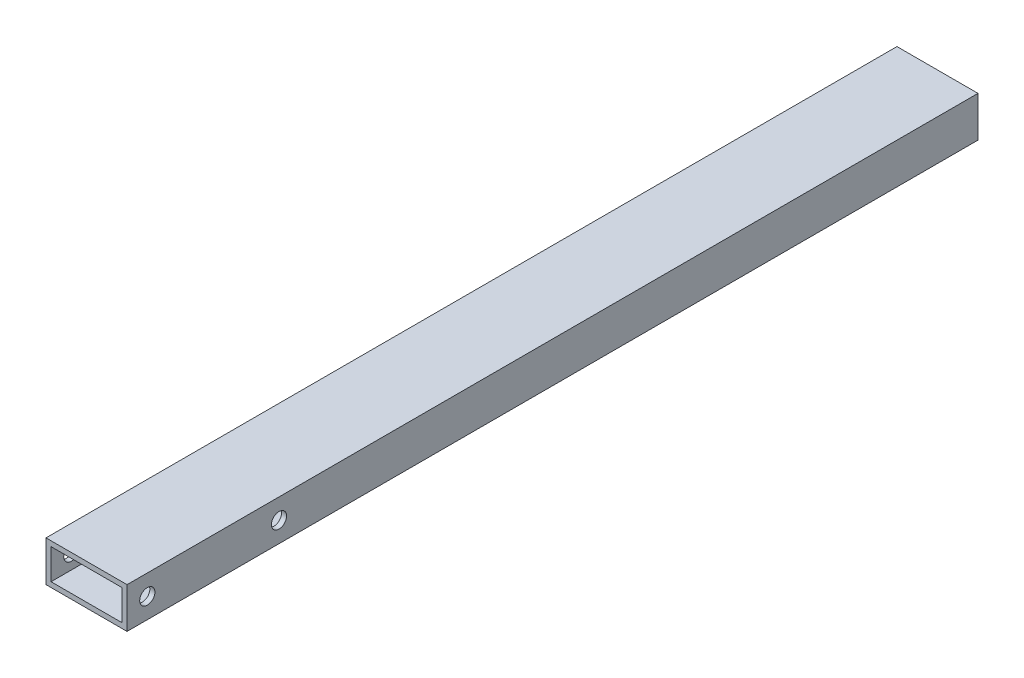
SolidWorks part; units mm, degrees
ref_plane "Front Plane" through (0, 0, 0) normal (0, 0, 1) x (1, 0, 0)
ref_plane "Top Plane" through (0, 0, 0) normal (0, 1, 0) x (1, 0, 0)
ref_plane "Right Plane" through (0, 0, 0) normal (1, 0, 0) x (0, 0, -1)
sketch "Sketch1" plane through (0, 0, 0) normal (0, 0, 1) x (1, 0, 0)
  line L0 (-22.225, 9.525) -> (22.225, 9.525)
  line L1 (-25.4, -12.7) -> (25.4, -12.7)
  line L2 (-25.4, -12.7) -> (-25.4, 12.7)
  line L3 (-25.4, 12.7) -> (25.4, 12.7)
  line L4 (25.4, -12.7) -> (25.4, 12.7)
  line L5 (-25.4, -12.7) -> (25.4, 12.7) construction
  line L6 (-25.4, 12.7) -> (25.4, -12.7) construction
  line L7 (22.225, -9.525) -> (22.225, 9.525)
  line L8 (-22.225, -9.525) -> (22.225, -9.525)
  line L9 (-22.225, -9.525) -> (-22.225, 9.525)
  point P0 (0, 0)
  dimension "D1" = 25.4
  dimension "D2" = 50.8
  dimension "D3" = 3.175
extrude "Boss-Extrude1" add sketch "Sketch1" along normal blind 457.2
sketch "Sketch2" plane through (-25.4, 0, 0) normal (-1, 0, 0) x (0, 0, 1)
  line L0 (457.2, 0) -> (438.15, 0) construction
  line L1 (457.2, 12.7) -> (457.2, -12.7) construction
  circle A0 centre (438.15, 0) radius 4.7625
  dimension "D2" = 9.525
  dimension "D1" = 19.05
extrude "Cut-Extrude1" cut sketch "Sketch2" against normal through all
sketch "Sketch3" plane through (0, 0, 457.2) normal (0, 0, 1) x (1, 0, 0)
  line L0 (22.225, -9.525) -> (22.225, 9.525) construction
  line L1 (22.225, 9.525) -> (-22.225, 9.525) construction
  line L2 (-22.225, -9.525) -> (22.225, -9.525) construction
  line L3 (-22.225, 9.525) -> (-22.225, -9.525) construction
  line L4 (25.4, -12.7) -> (25.4, 12.7)
  line L5 (25.4, 12.7) -> (-25.4, 12.7)
  line L6 (-25.4, 12.7) -> (-25.4, -12.7)
  line L7 (-25.4, -12.7) -> (25.4, -12.7)
  line L8 (25.4, -12.7) -> (25.4, 12.7)
  line L9 (25.4, 12.7) -> (-25.4, 12.7)
  line L10 (-25.4, 12.7) -> (-25.4, -12.7)
  line L11 (-25.4, -12.7) -> (25.4, -12.7)
  line L12 (22.225, -9.525) -> (22.225, 9.525)
  line L13 (22.225, 9.525) -> (-22.225, 9.525)
  line L14 (-22.225, -9.525) -> (22.225, -9.525)
  line L15 (-22.225, 9.525) -> (-22.225, -9.525)
  dimension "D1" = 0
extrude "Boss-Extrude2" add sketch "Sketch3" along normal blind 76.2
sketch "Sketch4" plane through (-25.4, 0, 0) normal (-1, 0, 0) x (0, 0, 1)
  line L0 (533.4, 0) -> (520.7, 0) construction
  line L1 (533.4, 12.7) -> (533.4, -12.7) construction
  circle A0 centre (520.7, 0) radius 4.7625
  dimension "D2" = 9.525
  dimension "D1" = 12.7
extrude "Cut-Extrude2" cut sketch "Sketch4" against normal through all
